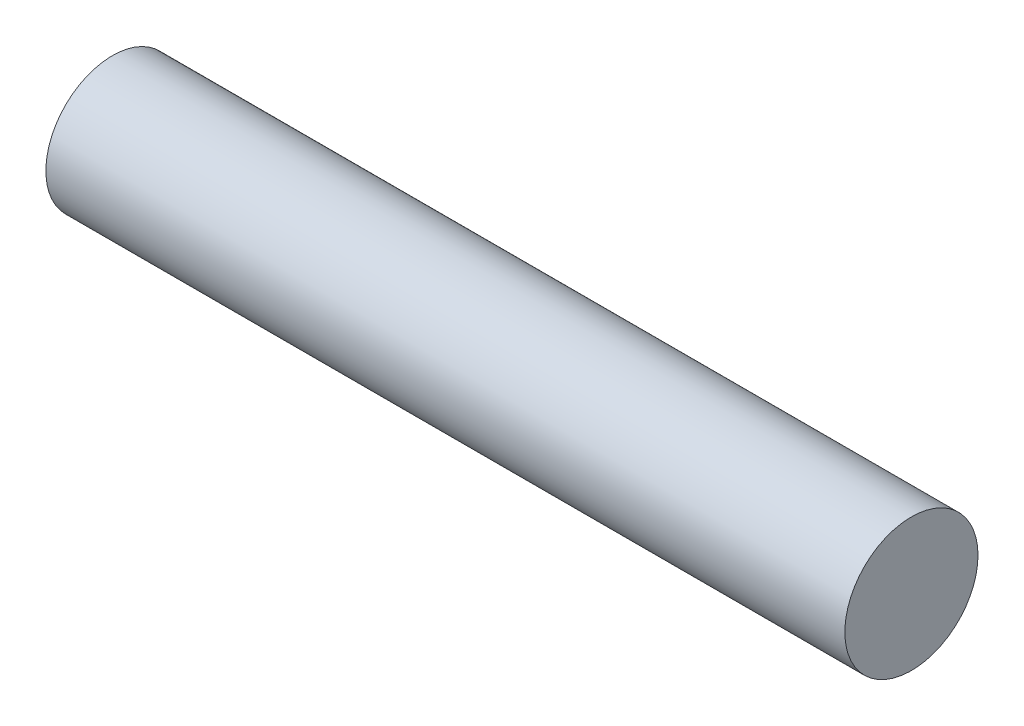
SolidWorks part; units mm, degrees
ref_plane "Front Plane" through (0, 0, 0) normal (0, 0, 1) x (1, 0, 0)
ref_plane "Top Plane" through (0, 0, 0) normal (0, 1, 0) x (1, 0, 0)
ref_plane "Right Plane" through (0, 0, 0) normal (1, 0, 0) x (0, 0, -1)
sketch "Sketch3" plane through (0, 0, 0) normal (1, 0, 0) x (0, 0, -1)
  circle A0 centre (0, 0) radius 2
  dimension "D1" = 4
extrude "Boss-Extrude1" add sketch "Sketch3" along normal blind 24
